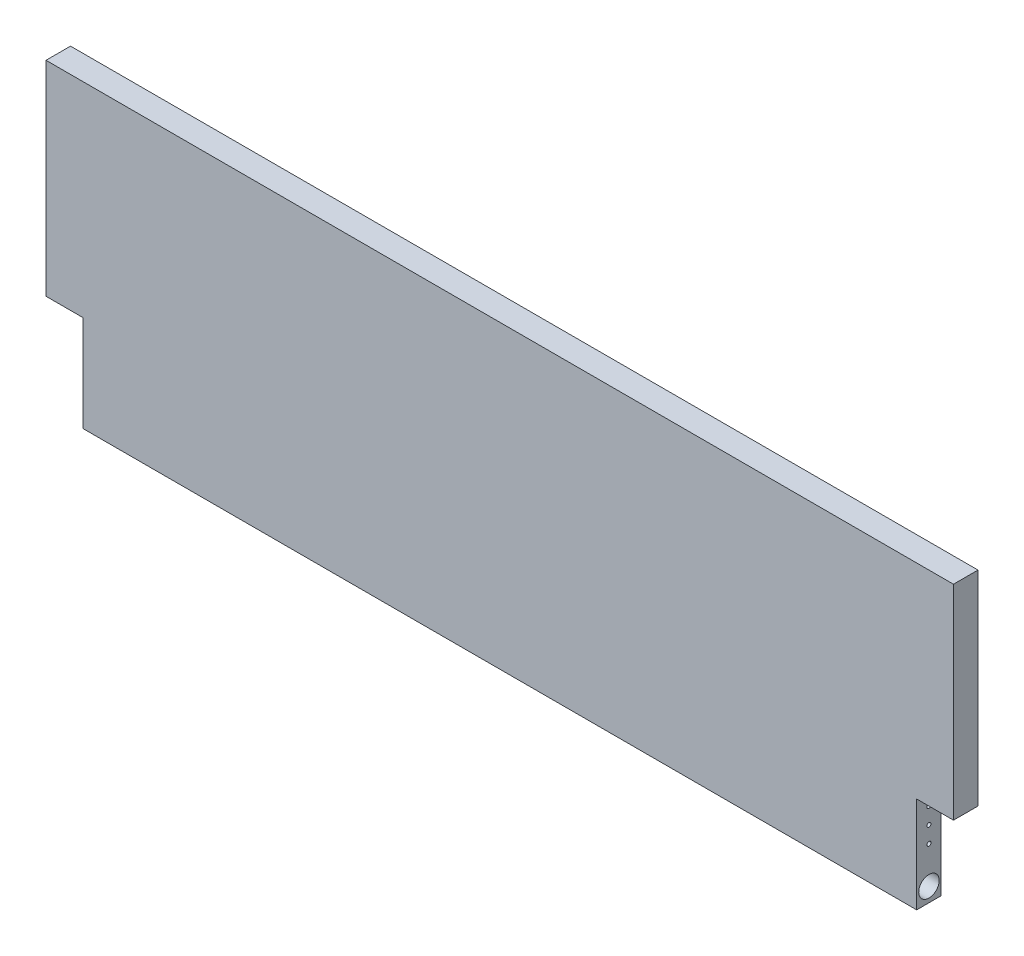
SolidWorks part; units mm, degrees
ref_plane "前视基准面" through (0, 0, 0) normal (0, 0, 1) x (1, 0, 0)
ref_plane "上视基准面" through (0, 0, 0) normal (0, 1, 0) x (1, 0, 0)
ref_plane "右视基准面" through (0, 0, 0) normal (1, 0, 0) x (0, 0, -1)
sketch "草图1" plane through (0, 0, 0) normal (1, 0, 0) x (0, 0, -1)
  line L2 (-3, 0) -> (-3, 70)
  line L3 (-3, 70) -> (3, 70)
  line L4 (3, 0) -> (3, 70)
  line L5 (-3, 0) -> (3, 70) construction
  line L6 (-3, 70) -> (3, 0) construction
  line L8 (-3, 0) -> (-3, -3.5)
  line L9 (-3, -3.5) -> (3, -3.5)
  line L10 (3, 0) -> (3, -3.5)
  line L11 (-3, 0) -> (3, -3.5) construction
  line L12 (-3, -3.5) -> (3, 0) construction
  point P7 (0, 35)
  point P8 (3, 35)
  point P11 (0, -1.75)
  dimension "D1" = 70
  dimension "D3" = 3.5
  dimension "D2" = 6
extrude "凸台-拉伸1" add sketch "草图1" along normal mid plane 204
sketch "草图2" plane through (0, 0, -3) normal (0, 0, -1) x (-1, 0, 0)
  line L6 (102, 70) -> (111, 70)
  line L12 (102, 70) -> (102, 20)
  line L13 (102, 20) -> (111, 20)
  line L15 (111, 70) -> (111, 20)
  line L16 (102, 70) -> (111, 20) construction
  line L17 (102, 20) -> (111, 70) construction
  point P4 (106.5, 45)
  dimension "D1" = 9
  dimension "D2" = 50
extrude "凸台-拉伸2" add sketch "草图2" against normal blind 6
sketch "草图3" plane through (-102, 0, 0) normal (-1, 0, 0) x (0, 0, 1)
  circle A0 centre (0, 17) radius 0.5
  circle A1 centre (0, 0) radius 2.5
  circle A3 centre (0, 13) radius 0.5
  circle A4 centre (0, 9) radius 0.5
  dimension "D2" = 17
  dimension "D3" = 4
extrude "切除-拉伸1" cut sketch "草图3" against normal blind 10
mirror "镜向1" about plane through (0, 0, 0) normal (1, 0, 0) of "凸台-拉伸2", "切除-拉伸1"
